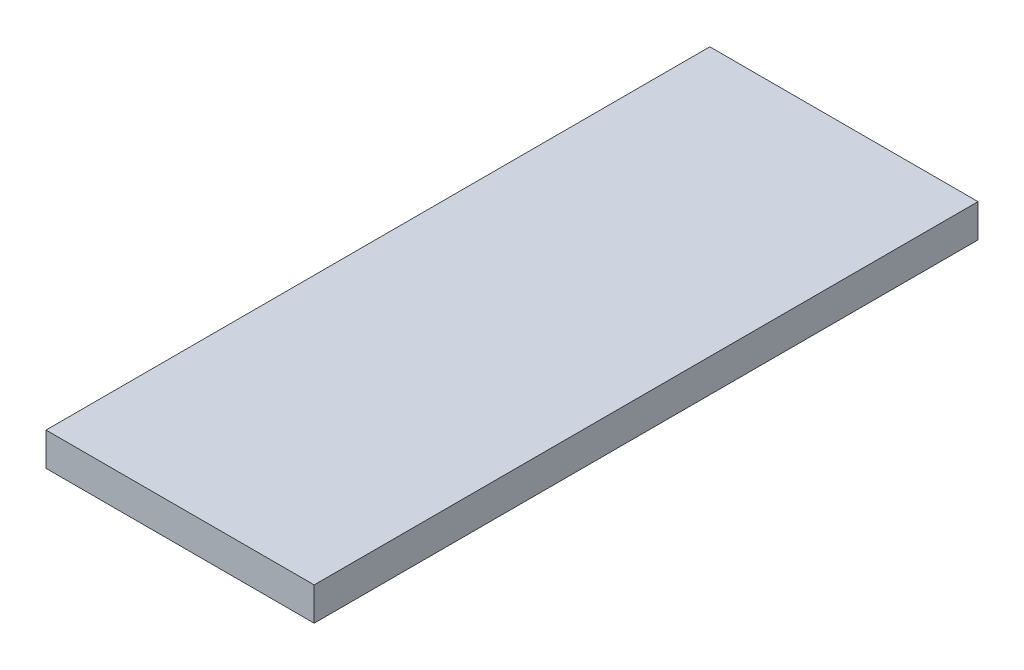
SolidWorks part; units mm, degrees
material "Glass"
ref_plane "Front Plane" through (0, 0, 0) normal (0, 0, 1) x (1, 0, 0)
ref_plane "Top Plane" through (0, 0, 0) normal (0, 1, 0) x (1, 0, 0)
ref_plane "Right Plane" through (0, 0, 0) normal (1, 0, 0) x (0, 0, -1)
sketch "Sketch1" plane through (0, 0, 0) normal (0, 1, 0) x (1, 0, 0)
  line L1 (-6.4135, -15.875) -> (6.4135, -15.875)
  line L2 (-6.4135, -15.875) -> (-6.4135, 15.875)
  line L3 (-6.4135, 15.875) -> (6.4135, 15.875)
  line L4 (6.4135, -15.875) -> (6.4135, 15.875)
  line L5 (-6.4135, -15.875) -> (6.4135, 15.875) construction
  line L6 (-6.4135, 15.875) -> (6.4135, -15.875) construction
  point P0 (0, 0)
  dimension "D1" = 31.75
  dimension "D2" = 12.827
extrude "Boss-Extrude1" add sketch "Sketch1" along normal blind 1.5875
